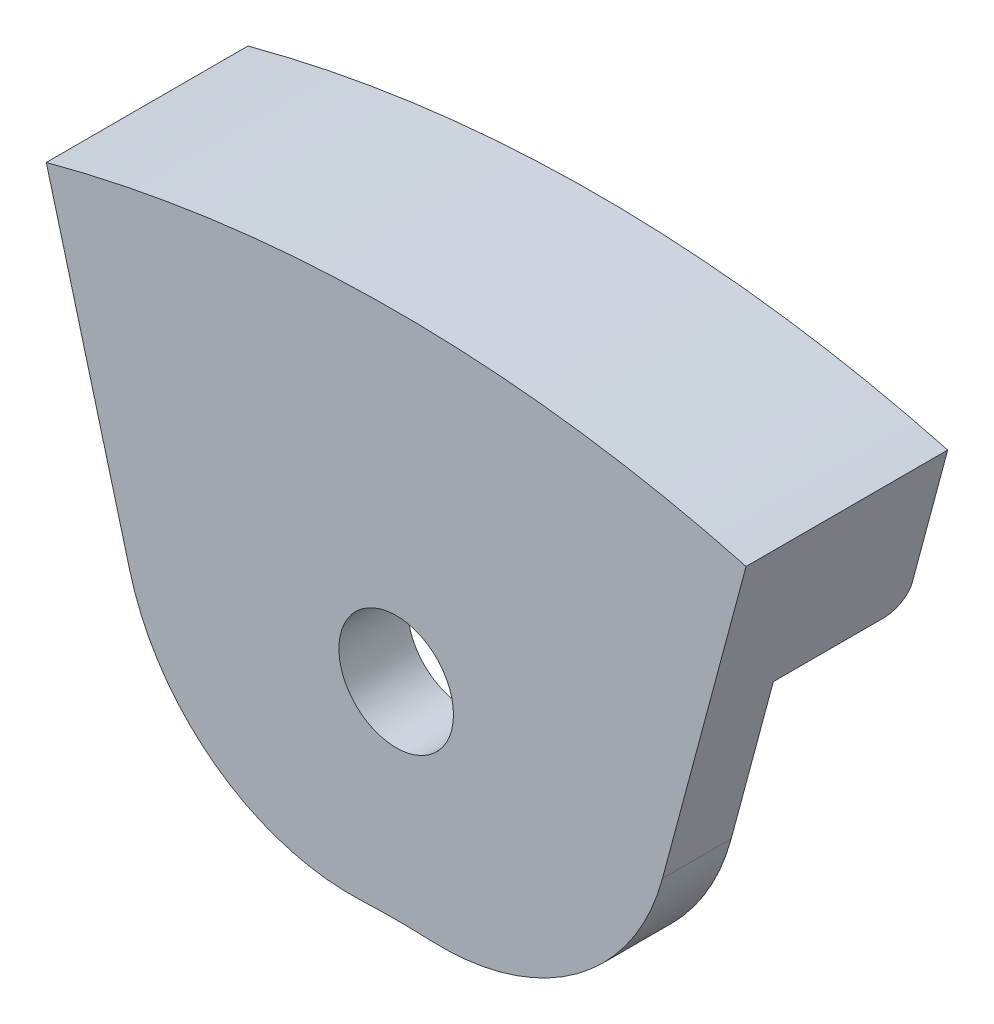
SolidWorks part; units mm, degrees
material "6061 合金"
ref_plane "前视基准面" through (0, 0, 0) normal (0, 0, 1) x (1, 0, 0)
ref_plane "上视基准面" through (0, 0, 0) normal (0, 1, 0) x (1, 0, 0)
ref_plane "右视基准面" through (0, 0, 0) normal (1, 0, 0) x (0, 0, -1)
sketch "草图1" plane through (0, 0, 0) normal (0, 0, 1) x (1, 0, 0)
  line L0 (-7.6352, 28.4948) -> (0, 0) construction
  line L1 (0, 0) -> (7.6352, 28.4948) construction
  line L2 (-7.6352, 28.4948) -> (-6.7293, 25.1141)
  line L3 (6.7293, 25.1141) -> (7.6352, 28.4948)
  arc A0 (-7.6352, 28.4948) -> (7.6352, 28.4948) centre (0, 0) cw
  arc A1 (-6.7293, 25.1141) -> (6.7293, 25.1141) centre (0, 0) cw
  point P6 (0, 29.5)
  point P7 (0, 26)
  dimension "D1" = 26
  dimension "D2" = 29.5
  dimension "D3" = 30
extrude "凸台-拉伸1" add sketch "草图1" along normal blind 2.9
sketch "草图2" plane through (0, 0, 2.9) normal (0, 0, 1) x (1, 0, 0)
  line L0 (-7.6352, 28.4948) -> (0, 0) construction
  line L1 (0, 0) -> (7.6352, 28.4948) construction
  line L2 (-7.6352, 28.4948) -> (-4.6587, 17.3867)
  line L3 (4.6587, 17.3867) -> (7.6352, 28.4948)
  arc A0 (7.6352, 28.4948) -> (-7.6352, 28.4948) centre (0, 0) ccw construction
  arc A1 (7.6352, 28.4948) -> (-7.6352, 28.4948) centre (0, 0) ccw
  arc A2 (-4.6587, 17.3867) -> (4.6587, 17.3867) centre (0, 0) cw
  circle A3 centre (0, 22.5) radius 1.25
  dimension "D1" = 18
  dimension "D2" = 2.5
  dimension "D3" = 22.5
extrude "凸台-拉伸2" add sketch "草图2" along normal blind 1.5
fillet "圆角1" radius 5 2 edges at (4.6587, 17.3867, 3.65) (-4.6587, 17.3867, 3.65)
fillet "圆角2" radius 0.5 1 edges at (0, 26, 0)
